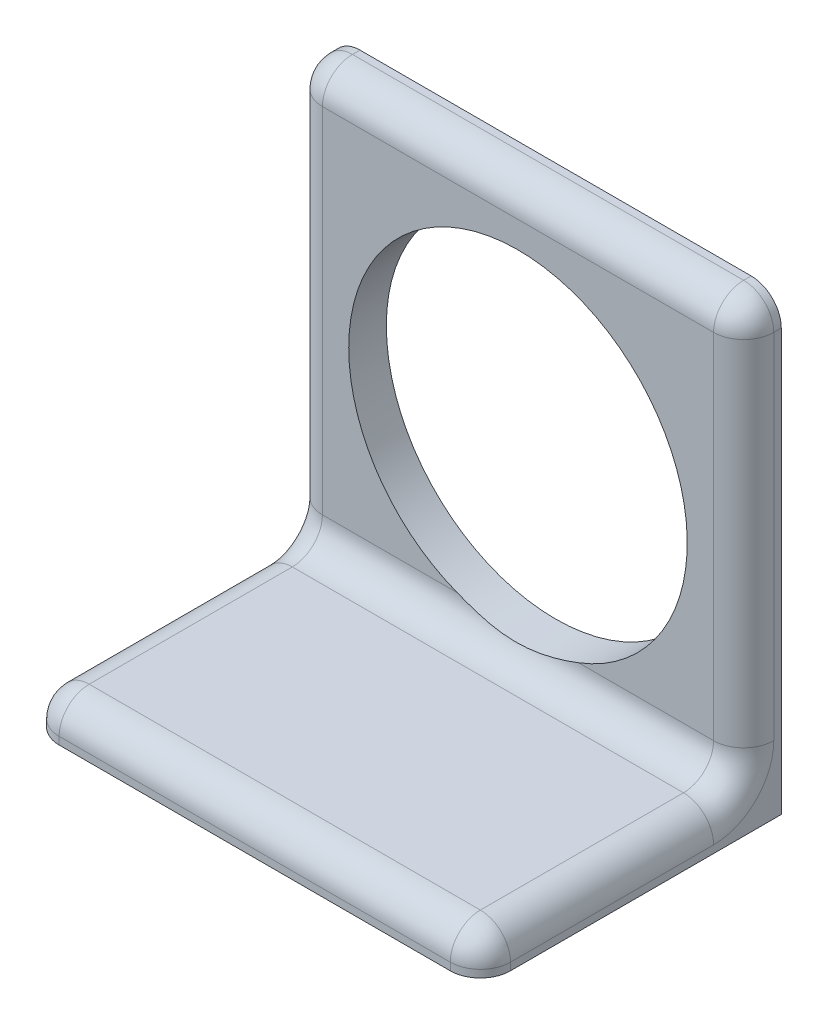
SolidWorks part; units mm, degrees
ref_plane "Front Plane" through (0, 0, 0) normal (0, 0, 1) x (1, 0, 0)
ref_plane "Top Plane" through (0, 0, 0) normal (0, 1, 0) x (1, 0, 0)
ref_plane "Right Plane" through (0, 0, 0) normal (1, 0, 0) x (0, 0, -1)
sketch "Sketch2" plane through (0, 0, 0) normal (0, 0, 1) x (1, 0, 0)
  line L1 (0, 0) -> (38.1, 0)
  line L2 (0, 0) -> (0, 38.1)
  line L3 (0, 38.1) -> (38.1, 38.1)
  line L4 (38.1, 0) -> (38.1, 38.1)
  dimension "D1" = 38.1
  dimension "D2" = 38.1
extrude "Boss-Extrude1" add sketch "Sketch2" along normal blind 3.175
sketch "Sketch3" plane through (0, 0, 3.175) normal (0, 0, 1) x (1, 0, 0)
  line L0 (38.1, 0) -> (38.1, 38.1) construction
  line L1 (0, 0) -> (38.1, 0)
  line L2 (0, 0) -> (0, 3.175)
  line L3 (0, 3.175) -> (38.1, 3.175)
  line L4 (38.1, 0) -> (38.1, 3.175)
  dimension "D1" = 3.175
extrude "Boss-Extrude2" add sketch "Sketch3" along normal blind 22.225
fillet "Fillet1" radius 2.54 11 edges at (19.05, 3.175, 25.4) (19.05, 38.1, 3.175) (0, 38.1, 1.5875) (38.1, 38.1, 1.5875) (0, 1.5875, 25.4) (38.1, 1.5875, 25.4)
sketch "Sketch4" plane through (0, 0, 0) normal (0, 0, -1) x (-1, 0, 0)
  line L0 (-38.1, 0) -> (-38.1, 35.56) construction
  line L1 (0, 0) -> (-38.1, 0) construction
  circle A0 centre (-19.05, 19.05) radius 14.2875
  dimension "D3" = 28.575
  dimension "D1" = 19.05
  dimension "D2" = 19.05
extrude "Cut-Extrude1" cut sketch "Sketch4" against normal through all
